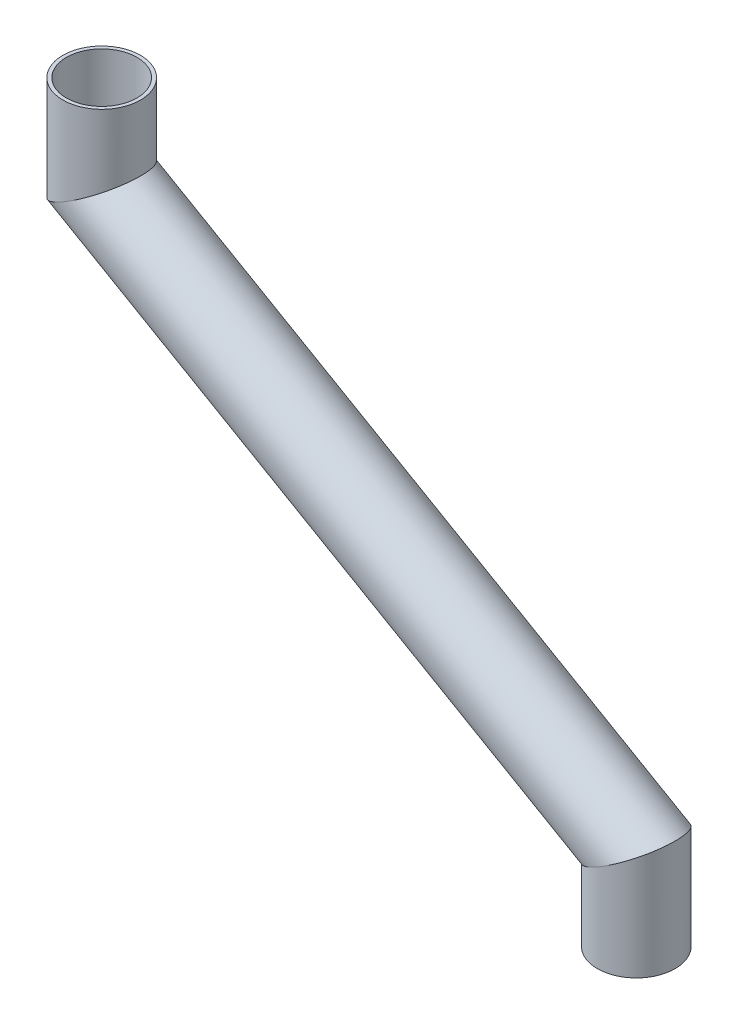
SolidWorks part; units mm, degrees
ref_plane "Front Plane" through (0, 0, 0) normal (0, 0, 1) x (1, 0, 0)
ref_plane "Top Plane" through (0, 0, 0) normal (0, 1, 0) x (1, 0, 0)
ref_plane "Right Plane" through (0, 0, 0) normal (1, 0, 0) x (0, 0, -1)
sketch "Sketch1" plane through (0, 0, 0) normal (0, 0, 1) x (1, 0, 0)
  line L0 (0, 57.6055) -> (0, 7.6055)
  line L1 (0, 7.6055) -> (303.1089, -167.3945)
  line L2 (303.1089, -167.3945) -> (303.1089, -217.3945)
  dimension "D1" = 350
  dimension "D2" = 50
  dimension "D3" = 50
ref_plane "Plane1" through (0, 50, 0) normal (0, 1, 0) x (1, 0, 0)
sketch "Sketch2" plane through (0, 50, 0) normal (0, 1, 0) x (1, 0, 0)
  circle A0 centre (0, 0) radius 20
  circle A1 centre (0, 0) radius 22
  dimension "D1" = 40
  dimension "D2" = 2
sweep "Sweep1" add profiles "Sketch2" path "Sketch1"
